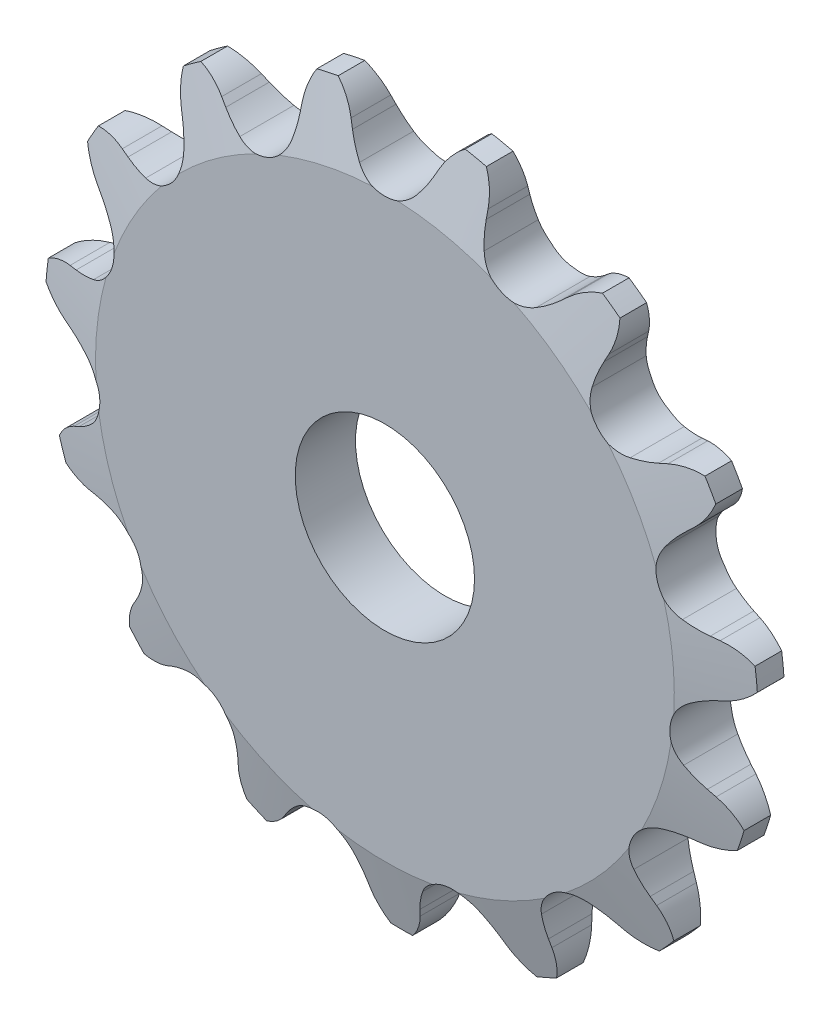
SolidWorks part; units mm, degrees
ref_plane "Front Plane" through (0, 0, 0) normal (0, 0, 1) x (1, 0, 0)
ref_plane "Top Plane" through (0, 0, 0) normal (0, 1, 0) x (1, 0, 0)
ref_plane "Right Plane" through (0, 0, 0) normal (1, 0, 0) x (0, 0, -1)
sketch "Sketch0" plane through (0, 0, 0) normal (0, 0, 1) x (1, 0, 0)
  line L0 (4.7625, -22.4058) -> (0, 0) construction
  line L1 (0, 0) -> (13.464, -18.5316) construction
  line L2 (0, 0) -> (-4.7625, -22.4058) construction
  line L3 (4.7625, -22.4058) -> (13.464, -18.5316) construction
  line L4 (4.7625, -22.4058) -> (-4.7625, -22.4058) construction
  line L5 (7.8768, -22.0376) -> (7.5383, -21.5839)
  line L6 (4.7625, -22.4058) -> (0, -23.4181) construction
  line L7 (1.7676, -23.3362) -> (1.8924, -22.784)
  line L8 (0, -22.4058) -> (0, -25.2633) construction
  line L9 (6.3929, -20.3924) -> (2.2049, -25.5641) construction
  line L10 (0, 0) -> (0, -22.4058) construction
  line L11 (7.5383, -21.5839) -> (2.2049, -25.5641) construction
  line L12 (0, -25.2633) -> (0, -25.9124) construction
  line L13 (11.2596, -19.5131) -> (7.8768, -22.0376) construction
  circle A0 centre (0, 0) radius 25.2633 construction
  circle A1 centre (0, 0) radius 22.9064 construction
  arc A2 (-2.7897, -26.6037) -> (13.3692, -23.1691) centre (0, 0) ccw
  circle A3 centre (0, 0) radius 25.9124 construction
  circle A4 centre (4.7625, -22.4058) radius 2.54 construction
  arc A7 (6.3929, -20.3924) -> (2.4541, -21.2296) centre (4.7625, -22.4058) ccw
  circle A8 centre (4.7625, -22.4058) radius 2.5908 construction
  arc A9 (7.8768, -22.0376) -> (13.3692, -23.1691) centre (11.2596, -19.5131) ccw
  arc A10 (7.5383, -21.5839) -> (6.3929, -20.3924) centre (2.2049, -25.5641) ccw
  arc A11 (1.7676, -23.3362) -> (-2.7897, -26.6037) centre (-2.3495, -22.4058) cw
  arc A12 (1.8924, -22.784) -> (2.4541, -21.2296) centre (8.3836, -24.2508) cw
  dimension "D1" = 2.5908
  dimension "R" = 2.5908
sketch "Sketch1" plane through (0, 0, 0) normal (1, 0, 0) x (0, 0, -1)
  line L0 (2.1336, 0) -> (-2.1336, 0)
  line L1 (-2.1336, 0) -> (-2.1336, 20.5008)
  line L2 (-2.1336, 20.5008) -> (-0.943, 25.2633)
  line L3 (-0.943, 25.2633) -> (0.943, 25.2633)
  line L4 (0.943, 25.2633) -> (2.1336, 20.5008)
  line L5 (2.1336, 20.5008) -> (2.1336, 0)
  line L7 (0, 25.2633) -> (0, 0) construction
  line L8 (-2.1336, 20.5008) -> (2.1336, 20.5008) construction
  line L9 (0, 25.2633) -> (0, -25.2633) construction
  line L10 (-2.1336, 20.5008) -> (-2.1336, 25.2633) construction
  line L11 (-2.1336, 25.2633) -> (-0.943, 25.2633) construction
  line L12 (0.943, 25.2633) -> (2.1336, 25.2633) construction
  line L13 (2.1336, 25.2633) -> (2.1336, 20.5008) construction
revolve "Revolve1" add sketch "Sketch1" angle 360 mid plane about L0
extrude "Cut-Extrude1" cut sketch "Sketch0" against normal through all and the other way through all
pattern_circular "CirPattern1" count 15 over 360 about axis through (0, 0, 0) along (0, 0, 1) of "Cut-Extrude1"
sketch "Sketch2" plane through (0, 0, 0) normal (0, 0, 1) x (1, 0, 0)
  circle A0 centre (0, 0) radius 6.35 construction
  circle A1 centre (0, 0) radius 30.1625
  circle A2 centre (0, 0) radius 25.273 construction
  dimension "Bore" = 12.7
  dimension "Hub Dia." = 60.325
  dimension "OD" = 50.546
sketch "Sketch3" plane through (0, 0, 0) normal (0, 0, 1) x (1, 0, 0)
  circle A0 centre (0, 0) radius 6.35 construction
  circle A1 centre (0, 0) radius 6.35
  circle A2 centre (0, 0) radius 25.273 construction
  circle A3 centre (0, 0) radius 25.273
extrude "Cut-Extrude2" cut sketch "Sketch3" along normal through all and the other way through all flip side to cut
equation "\"360/N@Sketch0\" = 360/\"Teeth@CirPattern1\""
equation "\"Ds@Sketch0\" = 1.005 * \"Dr@Sketch0\" + 0.003"
equation "\"R@Sketch0\" = 1/2 * \"Ds@Sketch0\""
equation "\"A@Sketch0\" = 35 +  ( 60 / \"Teeth@CirPattern1\" ) "
equation "\"B@Sketch0\" = 18 -  ( 56 / \"Teeth@CirPattern1\" )"
equation "\"ac@Sketch0\" = 0.8 * \"Dr@Sketch0\""
equation "\"ab@Sketch0\" = 1.4 * \"Dr@Sketch0\""
equation "\"J@Sketch0\" = 0.3 * \"Pitch@Sketch0\""
equation "\"h@Sketch1\" = \"Pitch@Sketch0\" / 2"
equation "\"g@Sketch1\" = \"h@Sketch1\" / 4"
